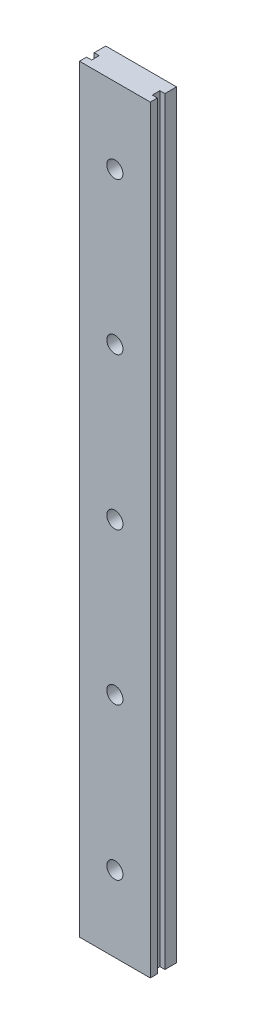
SolidWorks part; units mm, degrees
ref_plane "前视基准面" through (0, 0, 0) normal (0, 0, 1) x (1, 0, 0)
ref_plane "上视基准面" through (0, 0, 0) normal (0, 1, 0) x (1, 0, 0)
ref_plane "右视基准面" through (0, 0, 0) normal (1, 0, 0) x (0, 0, -1)
sketch "草图1" plane through (0, 0, 0) normal (0, 1, 0) x (1, 0, 0)
  line L0 (0, 0) -> (0, 1.4)
  line L1 (0, 1.4) -> (1, 1.4)
  line L2 (1, 1.4) -> (1, 2.9)
  line L3 (1, 2.9) -> (0, 2.9)
  line L4 (0, 2.9) -> (0, 5.2)
  line L5 (0, 5.2) -> (14, 5.2)
  line L6 (0, 0) -> (14, 0)
  line L7 (7, 5.2) -> (7, -2.1169) construction
  line L8 (14, 2.9) -> (14, 5.2)
  line L9 (13, 2.9) -> (14, 2.9)
  line L10 (13, 1.4) -> (13, 2.9)
  line L11 (14, 1.4) -> (13, 1.4)
  line L12 (14, 0) -> (14, 1.4)
  point P11 (7, 0)
  dimension "D1" = 5.2
  dimension "D2" = 14
  dimension "D3" = 1.5
  dimension "D4" = 2.3
  dimension "D5" = 1
extrude "凸台-拉伸1" add sketch "草图1" along normal blind 150
sketch "草图2" plane through (0, 0, -5.2) normal (0, 0, -1) x (-1, 0, 0)
  line L0 (-14, 0) -> (0, 0) construction
  line L1 (-7, 0) -> (-7, 187.5272) construction
  circle A0 centre (-7, 15) radius 1.6
  circle A1 centre (-7, 45) radius 1.6
  circle A2 centre (-7, 75) radius 1.6
  circle A3 centre (-7, 105) radius 1.6
  circle A4 centre (-7, 135) radius 1.6
  dimension "D1" = 3.2
  dimension "D2" = 15
  dimension "D3" = 5
extrude "切除-拉伸1" cut sketch "草图2" against normal through all
